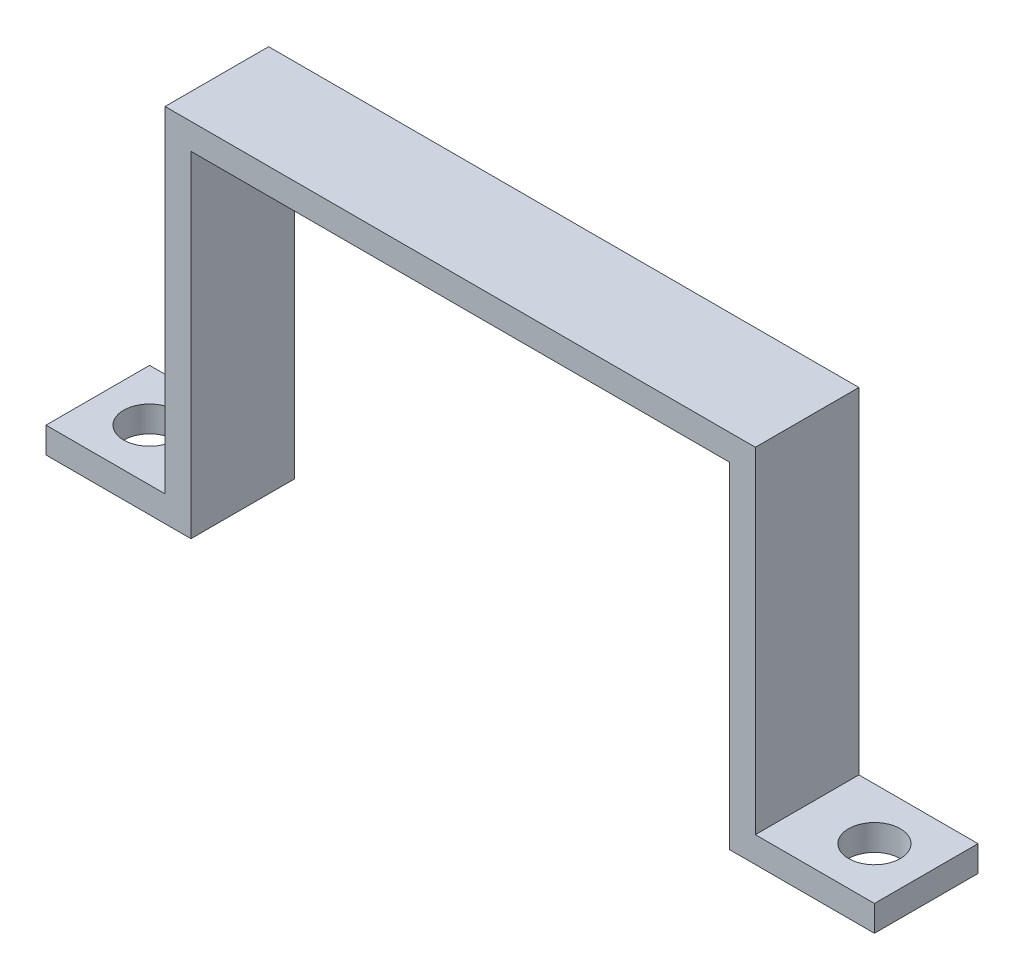
SolidWorks part; units mm, degrees
ref_plane "Front Plane" through (0, 0, 0) normal (0, 0, 1) x (1, 0, 0)
ref_plane "Top Plane" through (0, 0, 0) normal (0, 1, 0) x (1, 0, 0)
ref_plane "Right Plane" through (0, 0, 0) normal (1, 0, 0) x (0, 0, -1)
sketch "Sketch1" plane through (0, 0, 0) normal (0, 0, 1) x (1, 0, 0)
  line L0 (-16.51, 0) -> (16.51, 0)
  line L5 (16.51, 0) -> (16.51, -20.574)
  line L6 (16.51, -20.574) -> (25.4, -20.574)
  line L7 (0, 0) -> (0, 17.9837) construction
  line L8 (-16.51, -20.574) -> (-25.4, -20.574)
  line L9 (-16.51, 0) -> (-16.51, -20.574)
  dimension "D1" = 16.51
  dimension "D2" = 20.574
  dimension "D3" = 8.89
extrude "Extrude-Thin1" add sketch "Sketch1" along normal mid plane 6.35 thin thin type one direction wall 1.5875
sketch "Sketch2" plane through (0, -18.9865, 0) normal (0, 1, 0) x (1, 0, 0)
  line L0 (25.4, 3.175) -> (18.0975, 3.175) construction
  line L1 (25.4, -3.175) -> (25.4, 3.175) construction
  circle A0 centre (22.225, 0) radius 1.5875
  dimension "D1" = 3.175
  dimension "D2" = 3.175
extrude "Cut-Extrude1" cut sketch "Sketch2" against normal blind 2.54 contours A0
mirror "Mirror1" about plane through (0, 0, 0) normal (1, 0, 0) of "Cut-Extrude1"
